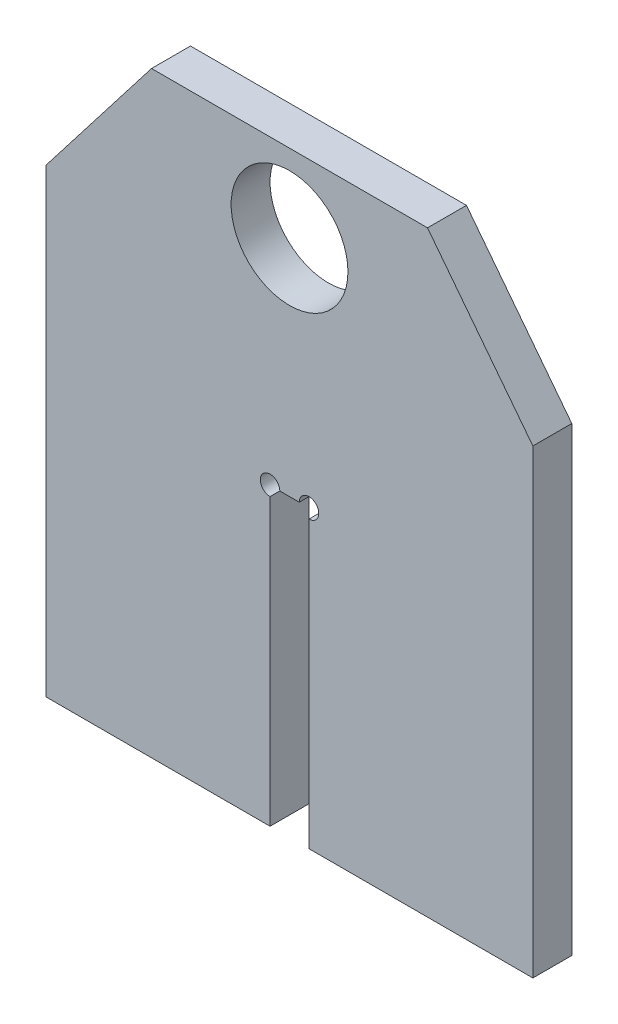
SolidWorks part; units mm, degrees
ref_plane "Front Plane" through (0, 0, 0) normal (0, 0, 1) x (1, 0, 0)
ref_plane "Top Plane" through (0, 0, 0) normal (0, 1, 0) x (1, 0, 0)
ref_plane "Right Plane" through (0, 0, 0) normal (1, 0, 0) x (0, 0, -1)
sketch "Sketch1" plane through (0, 0, 0) normal (0, 0, 1) x (1, 0, 0)
  line L0 (-37.5, -9) -> (-21.2655, 12)
  line L2 (-37.5, -9) -> (-37.5, -80)
  line L3 (-37.5, -80) -> (-3, -80)
  line L4 (37.5, -9) -> (37.5, -80)
  line L5 (37.5, -9) -> (21.2655, 12)
  line L6 (0, 12) -> (0, -80) construction
  line L7 (3, -80) -> (37.5, -80)
  line L9 (3, -80) -> (3, -36)
  line L10 (1.5, -34.5) -> (-1.5, -34.5)
  line L11 (-3, -80) -> (-3, -36)
  line L12 (-21.2655, 12) -> (21.2655, 12)
  circle A0 centre (0, 0) radius 9
  arc A1 (-1.5, -34.5) -> (-3, -36) centre (-3, -34.5) ccw
  arc A2 (3, -36) -> (1.5, -34.5) centre (3, -34.5) ccw
  dimension "D5" = 18
  dimension "D9" = 3
  dimension "D2" = 92
  dimension "D3" = 71
  dimension "D4" = 12
  dimension "D6" = 42.5309
  dimension "D7" = 45.5
  dimension "D8" = 6
  dimension "D10" = 3
  dimension "D11" = 75
extrude "Boss-Extrude1" add sketch "Sketch1" along normal blind 6
